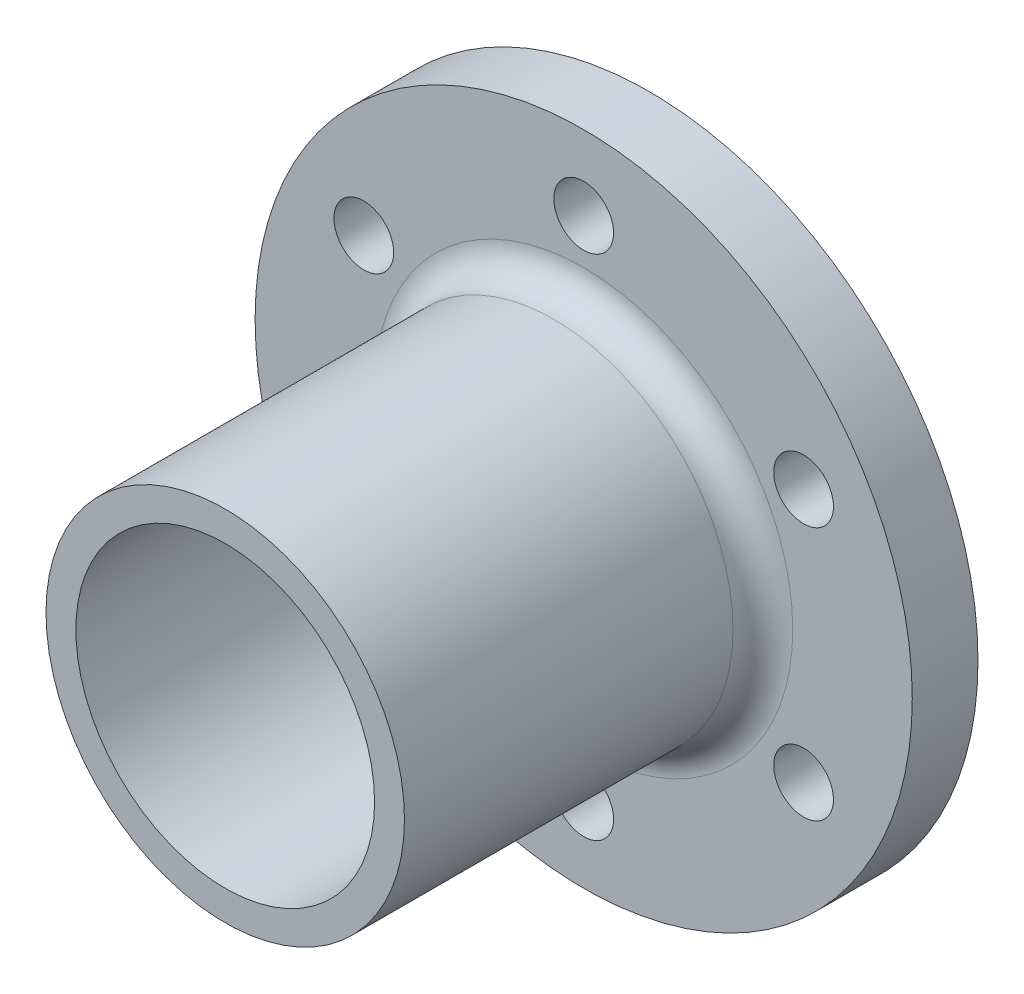
SolidWorks part; units mm, degrees
material "Ductile Iron"
ref_plane "Front Plane" through (0, 0, 0) normal (0, 0, 1) x (1, 0, 0)
ref_plane "Top Plane" through (0, 0, 0) normal (0, 1, 0) x (1, 0, 0)
ref_plane "Right Plane" through (0, 0, 0) normal (1, 0, 0) x (0, 0, -1)
sketch "Sketch1" plane through (0, 0, 0) normal (0, 0, 1) x (1, 0, 0)
  circle A0 centre (0, 0) radius 110
  dimension "D1" = 220
extrude "Boss-Extrude1" add sketch "Sketch1" along normal blind 22
sketch "Sketch2" plane through (0, 0, 22) normal (0, 0, 1) x (1, 0, 0)
  circle A0 centre (0, 0) radius 60
  dimension "D1" = 120
extrude "Boss-Extrude2" add sketch "Sketch2" along normal blind 120
sketch "Sketch3" plane through (0, 0, 142) normal (0, 0, 1) x (1, 0, 0)
  circle A0 centre (0, 0) radius 50
  dimension "D1" = 100
extrude "Cut-Extrude1" cut sketch "Sketch3" against normal through all
sketch "Sketch4" plane through (0, 0, 22) normal (0, 0, 1) x (1, 0, 0)
  circle A0 centre (0, 85) radius 10
  circle A1 centre (73.6122, 42.5) radius 10
  circle A2 centre (73.6122, -42.5) radius 10
  circle A3 centre (0, -85) radius 10
  circle A4 centre (-73.6122, -42.5) radius 10
  circle A5 centre (-73.6122, 42.5) radius 10
  point P15 (0, 0)
  dimension "D1" = 20
  dimension "D2" = 85
  dimension "D3" = 6
extrude "Cut-Extrude2" cut sketch "Sketch4" against normal through all
fillet "Fillet1" radius 10 1 edges at (60, 0, 22)
